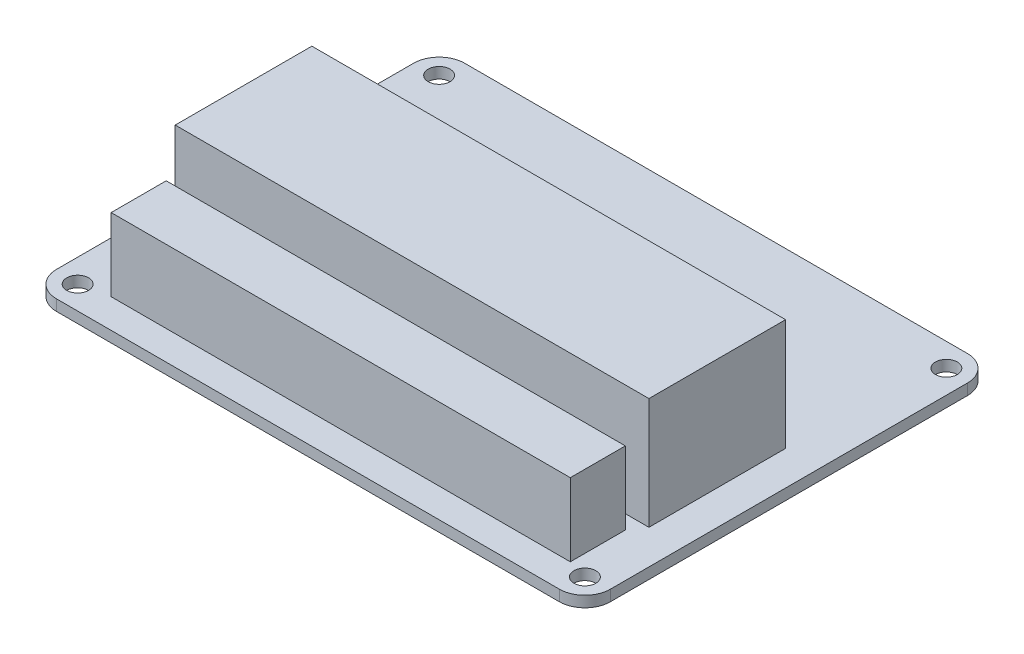
SolidWorks part; units mm, degrees
ref_plane "Front Plane" through (0, 0, 0) normal (0, 0, 1) x (1, 0, 0)
ref_plane "Top Plane" through (0, 0, 0) normal (0, 1, 0) x (1, 0, 0)
ref_plane "Right Plane" through (0, 0, 0) normal (1, 0, 0) x (0, 0, -1)
sketch "Sketch1" plane through (0, 0, 0) normal (0, 1, 0) x (1, 0, 0)
  line L0 (76, -28) -> (72.8, -28)
  line L1 (76, 0) -> (0, 0)
  line L2 (76, 0) -> (76, -56)
  line L3 (76, -56) -> (0, -56)
  line L4 (0, 0) -> (0, -56)
  line L5 (76, 0) -> (0, -56) construction
  line L6 (76, -56) -> (0, 0) construction
  line L7 (72.8, -52.8) -> (72.8, -3.2)
  line L8 (38, -56) -> (38, 0)
  line L9 (38, -56) -> (38, -51.9)
  circle A0 centre (72.8, -52.8) radius 1.5
  circle A1 centre (72.8, -3.2) radius 1.5
  circle A2 centre (3.2, -3.2) radius 1.5
  circle A3 centre (3.2, -52.8) radius 1.5
  point P0 (38, -28)
  point P10 (72.8, -28)
  dimension "D3" = 3.2
  dimension "D1" = 76
  dimension "D2" = 56
  dimension "D4" = 4.1
extrude "Boss-Extrude1" add sketch "Sketch1" along normal blind 1.5
fillet "Fillet1" radius 3.5 4 edges at (76, 0.75, 0) (76, 0.75, 56) (0, 0.75, 56) (0, 0.75, 0)
sketch "Sketch3" plane through (0, 1.5, 0) normal (0, 1, 0) x (1, 0, 0)
  line L1 (76, -56) -> (70, -56)
  line L2 (76, -56) -> (76, -52)
  line L3 (76, -52) -> (70, -52)
  line L4 (70, -56) -> (70, -52)
  line L5 (70, -52) -> (7, -52)
  line L6 (70, -52) -> (70, -44.45)
  line L7 (70, -44.45) -> (7, -44.45)
  line L8 (7, -52) -> (7, -44.45)
  dimension "D1" = 6
  dimension "D2" = 4
  dimension "D3" = 63
  dimension "D4" = 7.55
extrude "Boss-Extrude3" add sketch "Sketch3" along normal blind 10 contours L8 L5 L6 L7
sketch "Sketch4" plane through (0, 1.5, 0) normal (0, 1, 0) x (1, 0, 0)
  line L1 (76.0141, -56.0054) -> (71.2941, -56.0054)
  line L2 (76.0141, -56.0054) -> (76.0141, -42.5054)
  line L3 (76.0141, -42.5054) -> (71.2941, -42.5054)
  line L4 (71.2941, -56.0054) -> (71.2941, -42.5054)
  line L5 (71.2941, -42.5054) -> (6.2941, -42.5054)
  line L6 (71.2941, -42.5054) -> (71.2941, -23.7554)
  line L7 (71.2941, -23.7554) -> (6.2941, -23.7554)
  line L8 (6.2941, -42.5054) -> (6.2941, -23.7554)
  dimension "D1" = 4.72
  dimension "D2" = 13.5
  dimension "D3" = 65
  dimension "D4" = 18.75
extrude "Boss-Extrude4" add sketch "Sketch4" along normal blind 15.3 contours L8 L5 L6 L7
